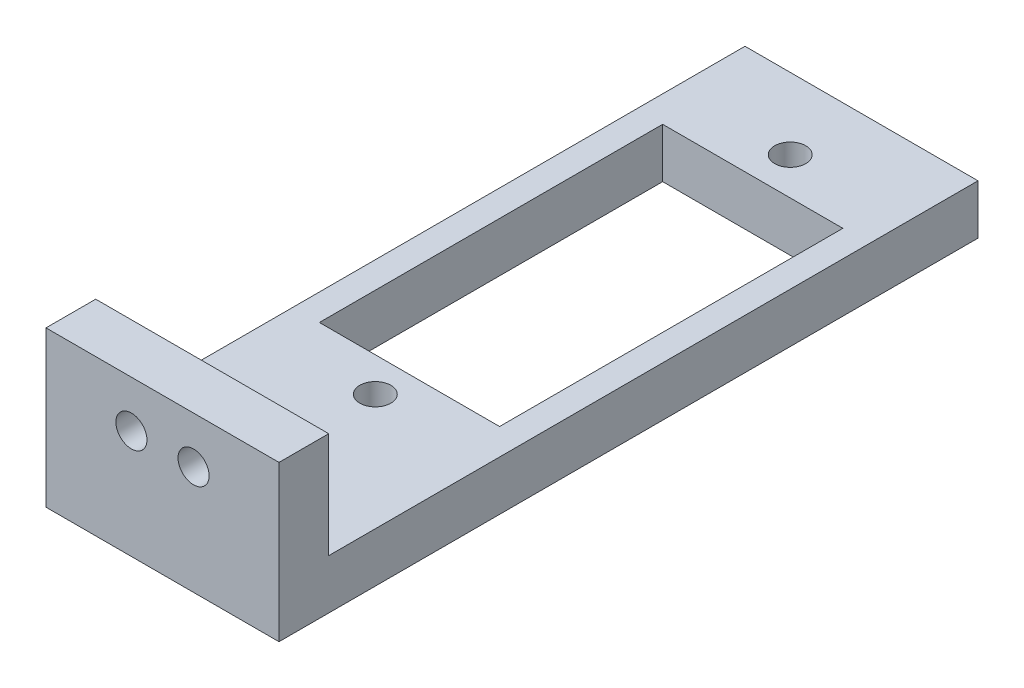
SolidWorks part; units mm, degrees
ref_plane "Front Plane" through (0, 0, 0) normal (0, 0, 1) x (1, 0, 0)
ref_plane "Top Plane" through (0, 0, 0) normal (0, 1, 0) x (1, 0, 0)
ref_plane "Right Plane" through (0, 0, 0) normal (1, 0, 0) x (0, 0, -1)
sketch "Sketch1" plane through (0, 0, 0) normal (0, 1, 0) x (1, 0, 0)
  line L1 (-7.5, 22.5) -> (7.5, 22.5)
  line L2 (-7.5, 22.5) -> (-7.5, -22.5)
  line L3 (-7.5, -22.5) -> (7.5, -22.5)
  line L4 (7.5, 22.5) -> (7.5, -22.5)
  line L5 (-7.5, 22.5) -> (7.5, -22.5) construction
  line L6 (-7.5, -22.5) -> (7.5, 22.5) construction
  point P0 (0, 0)
  dimension "D1" = 15
  dimension "D2" = 45
extrude "Boss-Extrude1" add sketch "Sketch1" along normal blind 10
sketch "Sketch4" plane through (0, 0, -22.5) normal (0, 0, -1) x (-1, 0, 0)
  line L0 (-7.5, 10) -> (-7.5, 0) construction
  line L1 (-7.5, 3.2) -> (7.5, 3.2)
  line L2 (-7.5, 3.2) -> (-7.5, 10)
  line L3 (-7.5, 10) -> (7.5, 10)
  line L4 (7.5, 3.2) -> (7.5, 10)
  dimension "D1" = 6.8
extrude "Cut-Extrude2" cut sketch "Sketch4" against normal blind 41.8
sketch "Sketch5" plane through (0, 0, 22.5) normal (0, 0, 1) x (1, 0, 0)
  line L1 (-7.5, 10) -> (7.5, 10) construction
  line L3 (-7.5, 10) -> (-7.5, 0) construction
  circle A0 centre (-2, 7) radius 1
  circle A1 centre (2, 7) radius 1
  dimension "D1" = 2
  dimension "D2" = 2
  dimension "D3" = 3
  dimension "D4" = 0
  dimension "D5" = 4
  dimension "D6" = 5.5
extrude "Cut-Extrude3" cut sketch "Sketch5" against normal through all
sketch "Sketch6" plane through (0, 3.2, 0) normal (0, 1, 0) x (1, 0, 0)
  line L1 (5.8, 15.5) -> (-5.8, 15.5)
  line L2 (5.8, 15.5) -> (5.8, -6.6)
  line L3 (5.8, -6.6) -> (-5.8, -6.6)
  line L4 (-5.8, 15.5) -> (-5.8, -6.6)
  line L5 (5.8, 15.5) -> (-5.8, -6.6) construction
  line L6 (5.8, -6.6) -> (-5.8, 15.5) construction
  line L9 (7.5, -19.3) -> (7.5, 22.5) construction
  line L11 (7.5, 22.5) -> (-7.5, 22.5) construction
  circle A0 centre (0, -8.8) radius 1
  circle A1 centre (0, 17.91) radius 1
  dimension "D5" = 2
  dimension "D6" = 2
  dimension "D7" = 2.2
  dimension "D8" = 2.41
  dimension "D1" = 11.6
  dimension "D2" = 22.1
  dimension "D3" = 1.7
  dimension "D4" = 7
extrude "Cut-Extrude4" cut sketch "Sketch6" against normal through all
